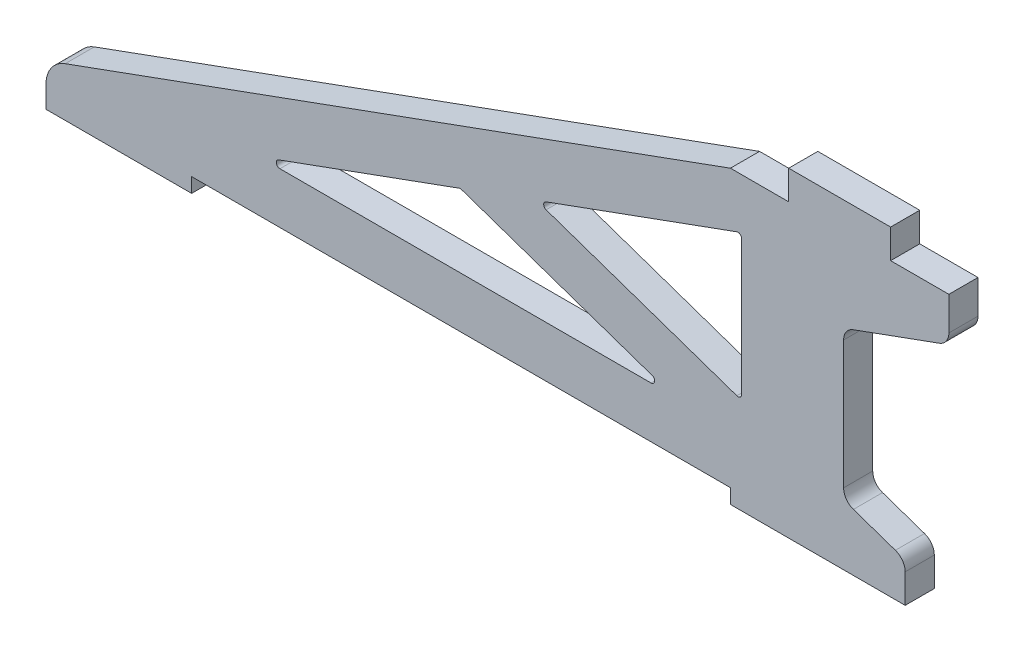
SolidWorks part; units mm, degrees
ref_plane "Front Plane" through (0, 0, 0) normal (0, 0, 1) x (1, 0, 0)
ref_plane "Top Plane" through (0, 0, 0) normal (0, 1, 0) x (1, 0, 0)
ref_plane "Right Plane" through (0, 0, 0) normal (1, 0, 0) x (0, 0, -1)
sketch "Sketch1" plane through (0, 0, 0) normal (0, 0, 1) x (1, 0, 0)
  line L0 (1.316, 3.3724) -> (47, 20)
  line L26 (47, 20) -> (51, 20)
  line L27 (51, 20) -> (51, 22)
  line L28 (51, 22) -> (58, 22)
  line L29 (58, 22) -> (58, 20)
  line L30 (58, 20) -> (62, 20)
  line L31 (62, 20) -> (62, 17.7002)
  line L32 (61.342, 16.7605) -> (55.4289, 14.6083)
  line L33 (54.771, 13.6686) -> (54.771, 4.8764)
  line L34 (55.4454, 3.9309) -> (58.3256, 2.9392)
  line L35 (59, 1.9937) -> (59, 0)
  line L36 (59, 0) -> (47, 0)
  line L37 (47, 0) -> (47, 1)
  line L38 (47, 1) -> (10, 1)
  line L39 (10, 1) -> (10, 0)
  line L40 (10, 0) -> (0, 0)
  line L41 (0, 0) -> (0, 6) construction
  line L43 (15.9797, 4.9849) -> (28.3679, 9.4938)
  line L44 (28.5348, 9.4953) -> (41.6296, 4.9864)
  line L45 (41.5482, 4.5) -> (16.0652, 4.5)
  line L46 (47.771, 16.1989) -> (47.771, 6.9239)
  line L47 (47.4396, 6.6875) -> (34.3447, 11.1964)
  line L48 (34.3406, 11.6677) -> (47.4355, 16.4339)
  line L49 (3.7198, 5.8334) -> (-4.4216, 5.8334) construction
  line L52 (0, 1.493) -> (0, 0)
  arc A0 (1.316, 3.3724) -> (0, 1.493) centre (2, 1.493) ccw
  arc A2 (47.771, 16.1989) -> (47.4355, 16.4339) centre (47.521, 16.1989) ccw
  arc A3 (47.771, 6.9239) -> (47.4396, 6.6875) centre (47.521, 6.9239) cw
  arc A4 (34.3447, 11.1964) -> (34.3406, 11.6677) centre (34.4261, 11.4328) cw
  arc A5 (28.3679, 9.4938) -> (28.5348, 9.4953) centre (28.4534, 9.2589) cw
  arc A6 (41.6296, 4.9864) -> (41.5482, 4.5) centre (41.5482, 4.75) cw
  arc A7 (15.9797, 4.9849) -> (16.0652, 4.5) centre (16.0652, 4.75) ccw
  arc A8 (58.3256, 2.9392) -> (59, 1.9937) centre (58, 1.9937) cw
  arc A9 (54.771, 4.8764) -> (55.4454, 3.9309) centre (55.771, 4.8764) ccw
  arc A10 (55.4289, 14.6083) -> (54.771, 13.6686) centre (55.771, 13.6686) ccw
  arc A11 (62, 17.7002) -> (61.342, 16.7605) centre (61, 17.7002) cw
  point P6 (0, 2.8934)
  point P40 (62, 17)
  dimension "D4" = 2
  dimension "D5" = 0.25
  dimension "D6" = 1
  dimension "D7" = 1
  dimension "D9" = 3.5
  dimension "D10" = 3.5
  dimension "D11" = 10
  dimension "D12" = 12
  dimension "D13" = 3.5
  dimension "D14" = 20
  dimension "D15" = 20
  dimension "D16" = 37
  dimension "D17" = 1
  dimension "D18" = 1
  dimension "D19" = 19
  dimension "D22" = 7
  dimension "D23" = 2
  dimension "D26" = 4
  dimension "D27" = 4
  dimension "D29" = 3
  dimension "D30" = 51
  dimension "D31" = 7
extrude "Boss-Extrude1" add sketch "Sketch1" along normal blind 2
